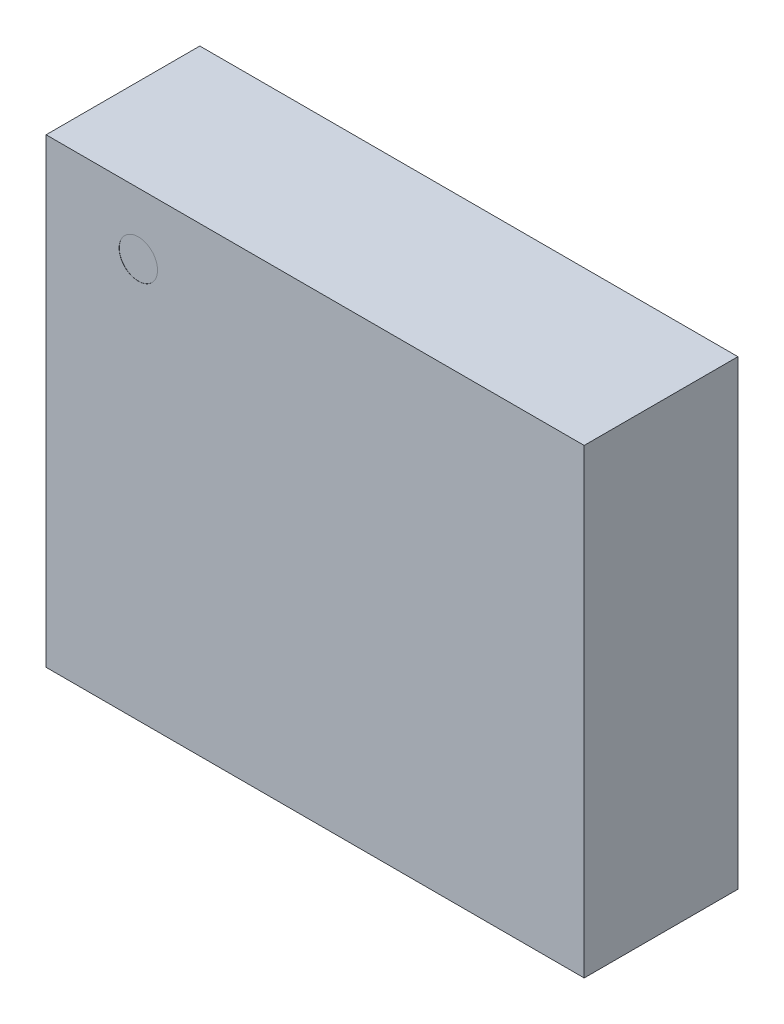
SolidWorks part; units mm, degrees
ref_plane "Front Plane" through (0, 0, 0) normal (0, 0, 1) x (1, 0, 0)
ref_plane "Top Plane" through (0, 0, 0) normal (0, 1, 0) x (1, 0, 0)
ref_plane "Right Plane" through (0, 0, 0) normal (1, 0, 0) x (0, 0, -1)
sketch "Sketch1" plane through (0, 0, 0) normal (0, 0, 1) x (1, 0, 0)
  line L1 (-1.75, -1.5) -> (1.75, -1.5)
  line L2 (-1.75, -1.5) -> (-1.75, 1.5)
  line L3 (-1.75, 1.5) -> (1.75, 1.5)
  line L4 (1.75, -1.5) -> (1.75, 1.5)
  line L5 (-1.75, -1.5) -> (1.75, 1.5) construction
  line L6 (-1.75, 1.5) -> (1.75, -1.5) construction
  point P0 (0, 0)
  dimension "D1" = 3.5
  dimension "D2" = 3
extrude "Boss-Extrude1" add sketch "Sketch1" along normal blind 1 contours L2 L1 L4 L3
sketch "Sketch2" plane through (0, 0, 0) normal (0, 0, -1) x (-1, 0, 0)
  line L0 (-1000, 0) -> (49000, 0) construction
  line L1 (0, -1000) -> (0, 49000) construction
  line L2 (1.75, 1.5) -> (-1.75, 1.5) construction
  line L3 (-0.33, 1.4) -> (-0.1, 1.4)
  line L4 (-0.33, 1.4) -> (-0.33, 1.05)
  line L5 (-0.33, 1.05) -> (-0.1, 1.05)
  line L6 (-0.1, 1.4) -> (-0.1, 1.05)
  line L7 (-0.33, 1.4) -> (-0.1, 1.05) construction
  line L8 (-0.33, 1.05) -> (-0.1, 1.4) construction
  line L9 (-0.76, 1.4) -> (-0.76, 1.05)
  line L10 (-0.76, 1.4) -> (-0.53, 1.4)
  line L11 (-0.53, 1.4) -> (-0.53, 1.05)
  line L12 (-0.76, 1.05) -> (-0.53, 1.05)
  line L13 (-1.19, 1.4) -> (-1.19, 1.05)
  line L14 (-1.19, 1.4) -> (-0.96, 1.4)
  line L15 (-0.96, 1.4) -> (-0.96, 1.05)
  line L16 (-1.19, 1.05) -> (-0.96, 1.05)
  line L17 (-1.62, 1.4) -> (-1.62, 1.05)
  line L18 (-1.62, 1.4) -> (-1.39, 1.4)
  line L19 (-1.39, 1.4) -> (-1.39, 1.05)
  line L20 (-1.62, 1.05) -> (-1.39, 1.05)
  line L21 (0.33, 1.05) -> (0.1, 1.05)
  line L22 (0.1, 1.4) -> (0.1, 1.05)
  line L23 (0.33, 1.4) -> (0.1, 1.4)
  line L24 (0.33, 1.4) -> (0.33, 1.05)
  line L25 (0.76, 1.4) -> (0.53, 1.4)
  line L26 (0.53, 1.4) -> (0.53, 1.05)
  line L27 (0.76, 1.05) -> (0.53, 1.05)
  line L28 (0.76, 1.4) -> (0.76, 1.05)
  line L29 (1.19, 1.4) -> (0.96, 1.4)
  line L30 (0.96, 1.4) -> (0.96, 1.05)
  line L31 (1.19, 1.05) -> (0.96, 1.05)
  line L32 (1.19, 1.4) -> (1.19, 1.05)
  line L33 (1.62, 1.4) -> (1.39, 1.4)
  line L34 (1.39, 1.4) -> (1.39, 1.05)
  line L35 (1.52, 1.05) -> (1.39, 1.05)
  line L36 (1.62, 1.4) -> (1.62, 1.15)
  line L37 (1.62, -1.4) -> (1.62, -1.05)
  line L38 (1.62, -1.05) -> (1.39, -1.05)
  line L39 (1.39, -1.4) -> (1.39, -1.05)
  line L40 (1.62, -1.4) -> (1.39, -1.4)
  line L41 (1.19, -1.4) -> (1.19, -1.05)
  line L42 (1.19, -1.05) -> (0.96, -1.05)
  line L43 (0.96, -1.4) -> (0.96, -1.05)
  line L44 (1.19, -1.4) -> (0.96, -1.4)
  line L45 (0.76, -1.4) -> (0.76, -1.05)
  line L46 (0.76, -1.05) -> (0.53, -1.05)
  line L47 (0.53, -1.4) -> (0.53, -1.05)
  line L48 (0.76, -1.4) -> (0.53, -1.4)
  line L49 (0.33, -1.4) -> (0.33, -1.05)
  line L50 (0.33, -1.4) -> (0.1, -1.4)
  line L51 (0.1, -1.4) -> (0.1, -1.05)
  line L52 (0.33, -1.05) -> (0.1, -1.05)
  line L53 (-0.33, -1.05) -> (-0.1, -1.05)
  line L54 (-0.1, -1.4) -> (-0.1, -1.05)
  line L55 (-0.33, -1.4) -> (-0.1, -1.4)
  line L56 (-0.33, -1.4) -> (-0.33, -1.05)
  line L57 (-0.76, -1.4) -> (-0.53, -1.4)
  line L58 (-0.53, -1.4) -> (-0.53, -1.05)
  line L59 (-0.76, -1.05) -> (-0.53, -1.05)
  line L60 (-0.76, -1.4) -> (-0.76, -1.05)
  line L61 (-1.19, -1.4) -> (-0.96, -1.4)
  line L62 (-0.96, -1.4) -> (-0.96, -1.05)
  line L63 (-1.19, -1.05) -> (-0.96, -1.05)
  line L64 (-1.19, -1.4) -> (-1.19, -1.05)
  line L65 (-1.62, -1.4) -> (-1.39, -1.4)
  line L66 (-1.39, -1.4) -> (-1.39, -1.05)
  line L67 (-1.62, -1.05) -> (-1.39, -1.05)
  line L68 (-1.62, -1.4) -> (-1.62, -1.05)
  line L69 (-1.65, 0.33) -> (-1.3, 0.33)
  line L70 (-1.65, 0.33) -> (-1.65, 0.1)
  line L71 (-1.65, 0.1) -> (-1.3, 0.1)
  line L72 (-1.3, 0.33) -> (-1.3, 0.1)
  line L73 (-1.65, 0.33) -> (-1.3, 0.1) construction
  line L74 (-1.65, 0.1) -> (-1.3, 0.33) construction
  line L75 (-1.75, -1.5) -> (-1.75, 1.5) construction
  line L76 (-1.65, 0.76) -> (-1.3, 0.76)
  line L77 (-1.3, 0.76) -> (-1.3, 0.53)
  line L78 (-1.65, 0.53) -> (-1.3, 0.53)
  line L79 (-1.65, 0.76) -> (-1.65, 0.53)
  line L80 (-1.65, -0.33) -> (-1.65, -0.1)
  line L81 (-1.65, -0.1) -> (-1.3, -0.1)
  line L82 (-1.3, -0.33) -> (-1.3, -0.1)
  line L83 (-1.65, -0.33) -> (-1.3, -0.33)
  line L84 (-1.65, -0.76) -> (-1.65, -0.53)
  line L85 (-1.65, -0.53) -> (-1.3, -0.53)
  line L86 (-1.3, -0.76) -> (-1.3, -0.53)
  line L87 (-1.65, -0.76) -> (-1.3, -0.76)
  line L88 (1.65, -0.76) -> (1.3, -0.76)
  line L89 (1.3, -0.76) -> (1.3, -0.53)
  line L90 (1.65, -0.53) -> (1.3, -0.53)
  line L91 (1.65, -0.76) -> (1.65, -0.53)
  line L92 (1.65, -0.33) -> (1.3, -0.33)
  line L93 (1.3, -0.33) -> (1.3, -0.1)
  line L94 (1.65, -0.1) -> (1.3, -0.1)
  line L95 (1.65, -0.33) -> (1.65, -0.1)
  line L96 (1.65, 0.33) -> (1.65, 0.1)
  line L97 (1.65, 0.1) -> (1.3, 0.1)
  line L98 (1.3, 0.33) -> (1.3, 0.1)
  line L99 (1.65, 0.33) -> (1.3, 0.33)
  line L100 (1.65, 0.76) -> (1.65, 0.53)
  line L101 (1.65, 0.53) -> (1.3, 0.53)
  line L102 (1.3, 0.76) -> (1.3, 0.53)
  line L103 (1.65, 0.76) -> (1.3, 0.76)
  line L104 (1.62, 1.15) -> (1.52, 1.05)
  point P4 (-0.215, 1.225)
  point P39 (1.62, 1.05)
  point P72 (-1.475, 0.215)
  dimension "D1" = 0.215
  dimension "D2" = 0.1
  dimension "D3" = 0.35
  dimension "D4" = 0.23
  dimension "D6" = 0.43
  dimension "D7" = 0.23
  dimension "D8" = 0.35
  dimension "D9" = 0.1
  dimension "D10" = 0.215
  dimension "D12" = 0.43
  dimension "D13" = 0.1
  dimension "D14" = 45
  dimension "D5" = 4
  dimension "D11" = 2
extrude "Boss-Extrude2" add sketch "Sketch2" against normal blind 0.13 and the other way blind 0.001 separate body
sketch "Sketch3" plane through (0, 0, 1) normal (0, 0, 1) x (1, 0, 0)
  line L0 (-1.75, -1.5) -> (-1.75, 1.5) construction
  line L1 (-1.75, 1.5) -> (1.75, 1.5) construction
  circle A0 centre (-1.15, 1.1) radius 0.125
  dimension "D1" = 0.25
  dimension "D2" = 0.6
  dimension "D3" = 0.4
extrude "Cut-Extrude1" cut sketch "Sketch3" against normal blind 0.001
equation "\"D6@Sketch2\"=2*\"D1@Sketch2\""
equation "\"D7@Sketch2\"=\"D4@Sketch2\""
equation "\"D8@Sketch2\"=\"D3@Sketch2\""
equation "\"D9@Sketch2\"=\"D2@Sketch2\""
equation "\"D10@Sketch2\"=\"D1@Sketch2\""
equation "\"D12@Sketch2\"=\"D6@Sketch2\""
